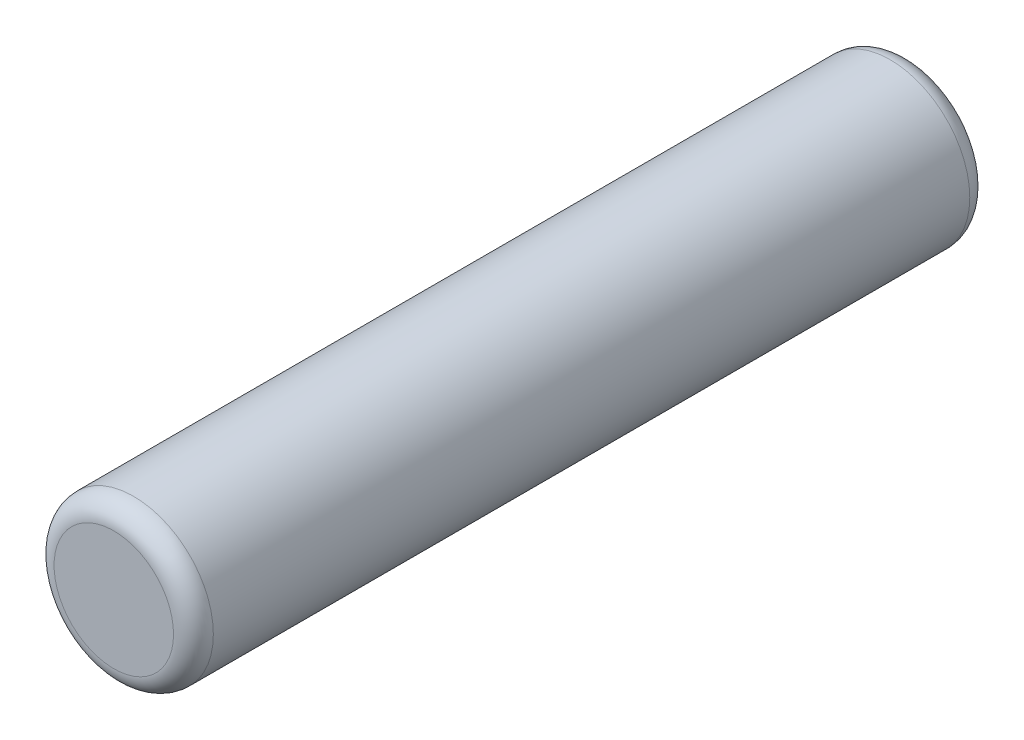
SolidWorks part; units mm, degrees
ref_plane "Plan de face" through (0, 0, 0) normal (0, 0, 1) x (1, 0, 0)
ref_plane "Plan de dessus" through (0, 0, 0) normal (0, 1, 0) x (1, 0, 0)
ref_plane "Plan de droite" through (0, 0, 0) normal (1, 0, 0) x (0, 0, -1)
sketch "Esquisse1" plane through (0, 0, 0) normal (0, 0, 1) x (1, 0, 0)
  circle A0 centre (0, 0) radius 1
  dimension "D1" = 2
extrude "Boss.-Extru.1" add sketch "Esquisse1" along normal blind 10
fillet "Congé1" radius 0.25 2 edges at (1, 0, 0) (1, 0, 10)
